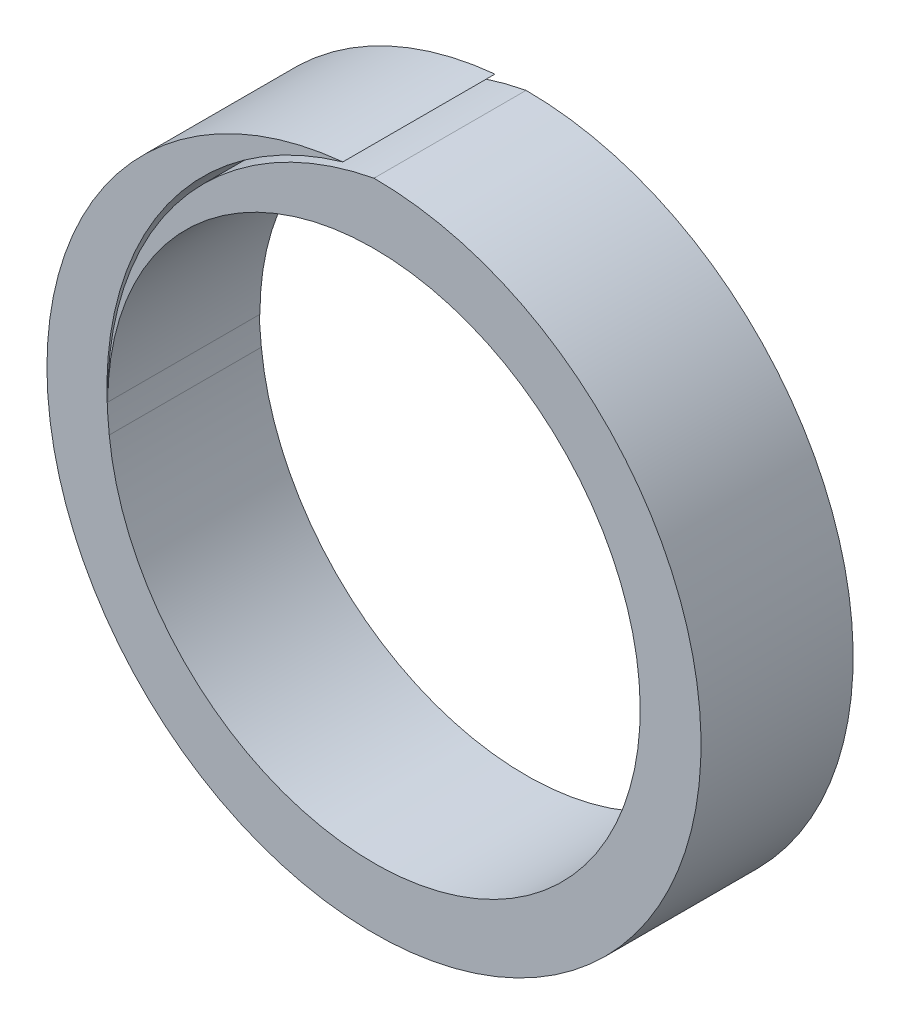
SolidWorks part; units mm, degrees
ref_plane "Front Plane" through (0, 0, 0) normal (0, 0, 1) x (1, 0, 0)
ref_plane "Top Plane" through (0, 0, 0) normal (0, 1, 0) x (1, 0, 0)
ref_plane "Right Plane" through (0, 0, 0) normal (1, 0, 0) x (0, 0, -1)
sketch "Sketch1" plane through (0, 0, 0) normal (0, 0, 1) x (1, 0, 0)
  arc A0 (-8.7023, -0.9126) -> (-8.75, 0) centre (0, 0) ccw
  arc A1 (-1.024, 10.7011) -> (0, 10.75) centre (0, 0) ccw
  arc A2 (0, 10.75) -> (-8.75, 0) centre (1.9984, 0.1874) ccw
  arc A3 (-8.7023, -0.9126) -> (-1.024, 10.7011) centre (1.9701, 0.3765) cw
  point P10 (-1.024, 10.75)
  dimension "D1" = 17.5
  dimension "D2" = 21.5
  dimension "D3" = 10.75
  dimension "D4" = 10.75
extrude "Boss-Extrude1" add sketch "Sketch1" along normal blind 5
